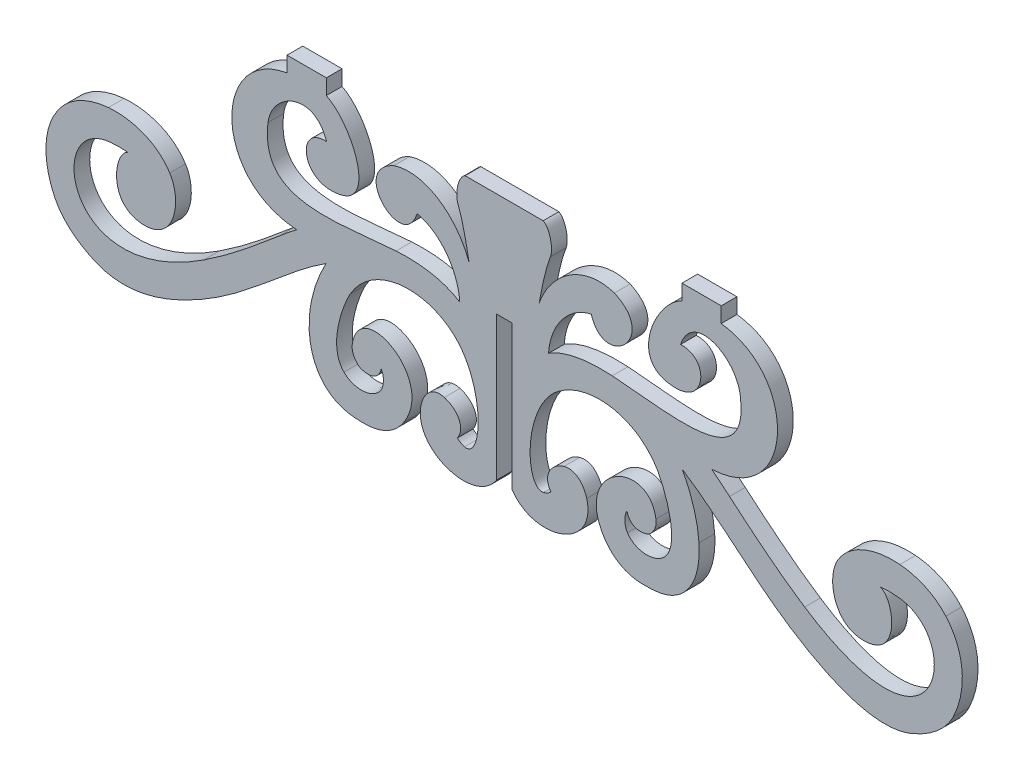
SolidWorks part; units mm, degrees
ref_plane "Plano frontal" through (0, 0, 0) normal (0, 0, 1) x (1, 0, 0)
ref_plane "Plano superior" through (0, 0, 0) normal (0, 1, 0) x (1, 0, 0)
ref_plane "Plano direito" through (0, 0, 0) normal (1, 0, 0) x (0, 0, -1)
sketch "Model" plane through (0, 0, 0) normal (0, 0, 1) x (1, 0, 0)
  line L0 (-6.7223, 87.0948) -> (1.611, 87.0948)
  line L3941 (25.0819, 87.0936) -> (25.0819, 89.0522)
  line L3942 (25.0819, 89.0522) -> (20.0819, 89.0522)
  line L3943 (20.0819, 89.0522) -> (20.0819, 87.0936)
  line L3944 (2.4147, 87.0948) -> (1.611, 87.0948)
  line L3947 (-6.7223, 87.0948) -> (-7.526, 87.0948)
  line L3948 (-25.1933, 87.0941) -> (-25.1933, 89.0522)
  line L3949 (-25.1933, 89.0522) -> (-30.1933, 89.0522)
  line L3950 (-30.1933, 89.0522) -> (-30.1933, 87.0941)
  line L3951 (-3.5557, 55.4934) -> (-3.5557, 73.8415)
  line L3952 (-3.5557, 73.8415) -> (-1.5557, 73.8415)
  line L3953 (-1.5557, 73.8415) -> (-1.5557, 55.4934)
  spline S78 degree 3 poles (-1.5557, 55.4934) (1.3324, 51.1828) (9.3145, 53.9302) (7.9628, 59.2514) knots 0 0 0 0 0.010753 0.010753 0.010753 0.010753
  spline S79 degree 3 poles (7.9628, 59.2514) (7.7655, 60.0281) (6.8767, 61.8404) (5.0534, 61.3244) knots 0.010753 0.010753 0.010753 0.010753 0.021505 0.021505 0.021505 0.021505
  spline S80 degree 3 poles (5.0534, 61.3244) (3.6461, 60.926) (2.2466, 59.35) (3.3931, 57.6868) knots 0.021505 0.021505 0.021505 0.021505 0.032258 0.032258 0.032258 0.032258
  spline S81 degree 3 poles (3.3931, 57.6868) (3.1478, 57.4328) (2.8154, 57.2407) (2.481, 57.1607) knots 0.032258 0.032258 0.032258 0.032258 0.043011 0.043011 0.043011 0.043011
  spline S82 degree 3 poles (2.481, 57.1607) (0.004, 56.5684) (-0.2039, 65.9986) (4.4458, 69.3227) knots 0.043011 0.043011 0.043011 0.043011 0.053763 0.053763 0.053763 0.053763
  spline S83 degree 3 poles (4.4458, 69.3227) (8.1489, 72.0987) (14.3081, 71.5264) (17.0509, 66.7244) knots 0.053763 0.053763 0.053763 0.053763 0.064516 0.064516 0.064516 0.064516
  spline S84 degree 3 poles (17.0509, 66.7244) (18.1854, 64.6611) (19.8274, 59.7153) (17.8402, 57.7253) knots 0.064516 0.064516 0.064516 0.064516 0.075269 0.075269 0.075269 0.075269
  spline S85 degree 3 poles (17.8402, 57.7253) (16.5822, 56.4654) (14.1497, 56.5444) (13.1448, 58.067) knots 0.075269 0.075269 0.075269 0.075269 0.086022 0.086022 0.086022 0.086022
  spline S86 degree 3 poles (13.1448, 58.067) (12.7434, 58.6752) (12.6969, 59.8398) (13.0959, 60.4397) knots 0.086022 0.086022 0.086022 0.086022 0.096774 0.096774 0.096774 0.096774
  spline S87 degree 3 poles (13.0959, 60.4397) (13.1597, 59.9829) (13.6899, 58.6489) (15.4964, 59.1291) knots 0.096774 0.096774 0.096774 0.096774 0.107527 0.107527 0.107527 0.107527
  spline S88 degree 3 poles (15.4964, 59.1291) (16.2163, 59.3056) (16.9538, 60.3437) (16.7747, 61.3853) knots 0.107527 0.107527 0.107527 0.107527 0.11828 0.11828 0.11828 0.11828
  spline S89 degree 3 poles (16.7747, 61.3853) (15.7027, 67.6161) (5.9938, 62.3947) (10.2507, 55.9445) knots 0.11828 0.11828 0.11828 0.11828 0.129032 0.129032 0.129032 0.129032
  spline S90 degree 3 poles (10.2507, 55.9445) (11.3104, 54.3388) (12.9835, 53.4391) (14.8163, 53.3639) knots 0.129032 0.129032 0.129032 0.129032 0.139785 0.139785 0.139785 0.139785
  spline S91 degree 3 poles (14.8163, 53.3639) (17.0037, 53.2741) (18.8296, 53.5898) (20.2685, 55.0308) knots 0.139785 0.139785 0.139785 0.139785 0.150538 0.150538 0.150538 0.150538
  spline S92 degree 3 poles (20.2685, 55.0308) (21.9316, 56.6963) (22.3987, 59.1658) (22.2511, 61.4956) knots 0.150538 0.150538 0.150538 0.150538 0.16129 0.16129 0.16129 0.16129
  spline S93 degree 3 poles (22.2511, 61.4956) (22.0962, 63.9402) (21.2748, 66.4447) (20.1166, 68.56) knots 0.16129 0.16129 0.16129 0.16129 0.172043 0.172043 0.172043 0.172043
  spline S94 degree 3 poles (20.1166, 68.56) (24.7894, 65.5652) (28.9378, 61.1957) (33.8482, 57.9913) knots 0.172043 0.172043 0.172043 0.172043 0.182796 0.182796 0.182796 0.182796
  spline S95 degree 3 poles (33.8482, 57.9913) (38.0156, 55.2717) (44.1924, 52.009) (49.1647, 53.947) knots 0.182796 0.182796 0.182796 0.182796 0.193548 0.193548 0.193548 0.193548
  spline S96 degree 3 poles (49.1647, 53.947) (51.3704, 54.8066) (53.5508, 56.3326) (54.6205, 58.5045) knots 0.193548 0.193548 0.193548 0.193548 0.204301 0.204301 0.204301 0.204301
  spline S97 degree 3 poles (54.6205, 58.5045) (56.2723, 61.8584) (56.3216, 66.11) (53.6788, 69.1304) knots 0.204301 0.204301 0.204301 0.204301 0.215054 0.215054 0.215054 0.215054
  spline S98 degree 3 poles (53.6788, 69.1304) (52.185, 70.8375) (49.9939, 71.7158) (47.8314, 71.902) knots 0.215054 0.215054 0.215054 0.215054 0.225806 0.225806 0.225806 0.225806
  spline S99 degree 3 poles (47.8314, 71.902) (44.993, 72.1464) (41.6526, 71.2075) (40.0071, 68.5733) knots 0.225806 0.225806 0.225806 0.225806 0.236559 0.236559 0.236559 0.236559
  spline S100 degree 3 poles (40.0071, 68.5733) (38.437, 66.1625) (39.309, 61.0858) (43.3399, 61.2103) knots 0.236559 0.236559 0.236559 0.236559 0.247312 0.247312 0.247312 0.247312
  spline S101 degree 3 poles (43.3399, 61.2103) (47.9822, 61.3536) (47.1577, 67.4304) (45.378, 68.1822) knots 0.247312 0.247312 0.247312 0.247312 0.258065 0.258065 0.258065 0.258065
  spline S102 degree 3 poles (45.378, 68.1822) (45.5771, 68.196) (46.0949, 68.3226) (47.5444, 68.1978) knots 0.258065 0.258065 0.258065 0.258065 0.268817 0.268817 0.268817 0.268817
  spline S103 degree 3 poles (47.5444, 68.1978) (56.1288, 67.4587) (53.2372, 49.7095) (35.7039, 61.1512) knots 0.268817 0.268817 0.268817 0.268817 0.27957 0.27957 0.27957 0.27957
  spline S104 degree 3 poles (35.7039, 61.1512) (32.3225, 63.358) (29.2308, 65.9343) (26.1424, 68.5597) knots 0.27957 0.27957 0.27957 0.27957 0.290323 0.290323 0.290323 0.290323
  spline S105 degree 3 poles (26.1424, 68.5597) (25.3878, 69.2011) (24.6507, 69.8283) (23.8569, 70.4159) knots 0.290323 0.290323 0.290323 0.290323 0.301075 0.301075 0.301075 0.301075
  spline S106 degree 3 poles (23.8569, 70.4159) (34.6371, 71.0038) (35.0189, 85.8605) (25.0819, 87.0936) knots 0.301075 0.301075 0.301075 0.301075 0.311828 0.311828 0.311828 0.311828
  spline S107 degree 3 poles (20.0819, 87.0936) (16.6077, 85.432) (12.9409, 77.0991) (19.324, 77.092) knots 0.344086 0.344086 0.344086 0.344086 0.354839 0.354839 0.354839 0.354839
  spline S108 degree 3 poles (19.324, 77.092) (23.2759, 77.0876) (23.5759, 82.3662) (19.9017, 82.1957) knots 0.354839 0.354839 0.354839 0.354839 0.365591 0.365591 0.365591 0.365591
  spline S109 degree 3 poles (19.9017, 82.1957) (21.4782, 86.8801) (26.9279, 84.3257) (27.5035, 80.4182) knots 0.365591 0.365591 0.365591 0.365591 0.376344 0.376344 0.376344 0.376344
  spline S110 degree 3 poles (27.5035, 80.4182) (28.8335, 71.3912) (18.3639, 73.948) (11.2069, 74.3959) knots 0.376344 0.376344 0.376344 0.376344 0.387097 0.387097 0.387097 0.387097
  spline S111 degree 3 poles (11.2069, 74.3959) (8.4975, 74.5655) (5.4129, 74.2948) (3.0953, 72.8221) knots 0.387097 0.387097 0.387097 0.387097 0.397849 0.397849 0.397849 0.397849
  spline S112 degree 3 poles (3.0953, 72.8221) (3.2894, 76.0459) (5.5232, 79.2191) (8.5335, 79.8535) knots 0.397849 0.397849 0.397849 0.397849 0.408602 0.408602 0.408602 0.408602
  spline S113 degree 3 poles (8.5335, 79.8535) (10.2661, 74.3684) (17.3019, 81.012) (11.4777, 83.6641) knots 0.408602 0.408602 0.408602 0.408602 0.419355 0.419355 0.419355 0.419355
  spline S114 degree 3 poles (11.4777, 83.6641) (7.6336, 84.9355) (3.4642, 82.1115) (1.9007, 77.7655) knots 0.419355 0.419355 0.419355 0.419355 0.430108 0.430108 0.430108 0.430108
  spline S115 degree 3 poles (1.9007, 77.7655) (2.1973, 79.4462) (2.7131, 82.0156) (3.3382, 83.5924) knots 0.430108 0.430108 0.430108 0.430108 0.44086 0.44086 0.44086 0.44086
  spline S116 degree 3 poles (3.3382, 83.5924) (3.7126, 84.5367) (3.2989, 86.6387) (2.4147, 87.0948) knots 0.44086 0.44086 0.44086 0.44086 0.451613 0.451613 0.451613 0.451613
  spline S118 degree 3 poles (-7.526, 87.0948) (-8.4102, 86.6387) (-8.8239, 84.5367) (-8.4495, 83.5924) knots 0.505376 0.505376 0.505376 0.505376 0.516129 0.516129 0.516129 0.516129
  spline S119 degree 3 poles (-8.4495, 83.5924) (-7.8244, 82.0156) (-7.3086, 79.4462) (-7.0121, 77.7655) knots 0.516129 0.516129 0.516129 0.516129 0.526882 0.526882 0.526882 0.526882
  spline S120 degree 3 poles (-7.0121, 77.7655) (-8.5755, 82.1115) (-12.7449, 84.9355) (-16.589, 83.6641) knots 0.526882 0.526882 0.526882 0.526882 0.537634 0.537634 0.537634 0.537634
  spline S121 degree 3 poles (-16.589, 83.6641) (-22.4132, 81.012) (-15.3774, 74.3684) (-13.6449, 79.8535) knots 0.537634 0.537634 0.537634 0.537634 0.548387 0.548387 0.548387 0.548387
  spline S122 degree 3 poles (-13.6449, 79.8535) (-10.6345, 79.2191) (-8.4007, 76.0459) (-8.2066, 72.8221) knots 0.548387 0.548387 0.548387 0.548387 0.55914 0.55914 0.55914 0.55914
  spline S123 degree 3 poles (-8.2066, 72.8221) (-10.5242, 74.2948) (-13.6088, 74.5655) (-16.3182, 74.3959) knots 0.55914 0.55914 0.55914 0.55914 0.569892 0.569892 0.569892 0.569892
  spline S124 degree 3 poles (-16.3182, 74.3959) (-23.4752, 73.948) (-33.7433, 71.3639) (-32.6149, 80.4182) knots 0.569892 0.569892 0.569892 0.569892 0.580645 0.580645 0.580645 0.580645
  spline S125 degree 3 poles (-32.6149, 80.4182) (-32.1511, 84.1391) (-26.7439, 86.7258) (-25.1674, 82.0414) knots 0.580645 0.580645 0.580645 0.580645 0.591398 0.591398 0.591398 0.591398
  spline S126 degree 3 poles (-25.1674, 82.0414) (-28.8415, 82.2119) (-28.5416, 76.9333) (-24.5897, 76.9377) knots 0.591398 0.591398 0.591398 0.591398 0.602151 0.602151 0.602151 0.602151
  spline S127 degree 3 poles (-24.5897, 76.9377) (-18.2058, 76.9448) (-21.7201, 85.433) (-25.1933, 87.0941) knots 0.602151 0.602151 0.602151 0.602151 0.612903 0.612903 0.612903 0.612903
  spline S128 degree 3 poles (-30.1933, 87.0941) (-39.689, 85.4201) (-39.8369, 71.1802) (-28.9683, 70.4159) knots 0.645161 0.645161 0.645161 0.645161 0.655914 0.655914 0.655914 0.655914
  spline S129 degree 3 poles (-28.9683, 70.4159) (-29.7621, 69.8283) (-30.4992, 69.2011) (-31.2537, 68.5597) knots 0.655914 0.655914 0.655914 0.655914 0.666667 0.666667 0.666667 0.666667
  spline S130 degree 3 poles (-31.2537, 68.5597) (-34.3422, 65.9343) (-37.4338, 63.358) (-40.8153, 61.1512) knots 0.666667 0.666667 0.666667 0.666667 0.677419 0.677419 0.677419 0.677419
  spline S131 degree 3 poles (-40.8153, 61.1512) (-58.3485, 49.7095) (-61.2401, 67.4587) (-52.6557, 68.1978) knots 0.677419 0.677419 0.677419 0.677419 0.688172 0.688172 0.688172 0.688172
  spline S132 degree 3 poles (-52.6557, 68.1978) (-51.2062, 68.3226) (-50.6884, 68.196) (-50.4894, 68.1822) knots 0.688172 0.688172 0.688172 0.688172 0.698925 0.698925 0.698925 0.698925
  spline S133 degree 3 poles (-50.4894, 68.1822) (-52.269, 67.4304) (-53.0935, 61.3536) (-48.4513, 61.2103) knots 0.698925 0.698925 0.698925 0.698925 0.709677 0.709677 0.709677 0.709677
  spline S134 degree 3 poles (-48.4513, 61.2103) (-44.4203, 61.0858) (-43.5483, 66.1625) (-45.1185, 68.5733) knots 0.709677 0.709677 0.709677 0.709677 0.72043 0.72043 0.72043 0.72043
  spline S135 degree 3 poles (-45.1185, 68.5733) (-46.764, 71.2075) (-50.1044, 72.1464) (-52.9427, 71.902) knots 0.72043 0.72043 0.72043 0.72043 0.731183 0.731183 0.731183 0.731183
  spline S136 degree 3 poles (-52.9427, 71.902) (-55.1052, 71.7158) (-57.2964, 70.8375) (-58.7901, 69.1304) knots 0.731183 0.731183 0.731183 0.731183 0.741935 0.741935 0.741935 0.741935
  spline S137 degree 3 poles (-58.7901, 69.1304) (-61.433, 66.11) (-61.3836, 61.8584) (-59.7318, 58.5045) knots 0.741935 0.741935 0.741935 0.741935 0.752688 0.752688 0.752688 0.752688
  spline S138 degree 3 poles (-59.7318, 58.5045) (-58.6621, 56.3326) (-56.4817, 54.8066) (-54.2761, 53.947) knots 0.752688 0.752688 0.752688 0.752688 0.763441 0.763441 0.763441 0.763441
  spline S139 degree 3 poles (-54.2761, 53.947) (-49.3037, 52.009) (-43.127, 55.2717) (-38.9596, 57.9913) knots 0.763441 0.763441 0.763441 0.763441 0.774194 0.774194 0.774194 0.774194
  spline S140 degree 3 poles (-38.9596, 57.9913) (-34.0491, 61.1957) (-29.9008, 65.5652) (-25.2279, 68.56) knots 0.774194 0.774194 0.774194 0.774194 0.784946 0.784946 0.784946 0.784946
  spline S141 degree 3 poles (-25.2279, 68.56) (-26.3861, 66.4447) (-27.2075, 63.9402) (-27.3624, 61.4956) knots 0.784946 0.784946 0.784946 0.784946 0.795699 0.795699 0.795699 0.795699
  spline S142 degree 3 poles (-27.3624, 61.4956) (-27.5101, 59.1658) (-27.0429, 56.6963) (-25.3799, 55.0308) knots 0.795699 0.795699 0.795699 0.795699 0.806452 0.806452 0.806452 0.806452
  spline S143 degree 3 poles (-25.3799, 55.0308) (-23.941, 53.5898) (-22.1151, 53.2741) (-19.9277, 53.3639) knots 0.806452 0.806452 0.806452 0.806452 0.817204 0.817204 0.817204 0.817204
  spline S144 degree 3 poles (-19.9277, 53.3639) (-18.0948, 53.4391) (-16.4217, 54.3388) (-15.362, 55.9445) knots 0.817204 0.817204 0.817204 0.817204 0.827957 0.827957 0.827957 0.827957
  spline S145 degree 3 poles (-15.362, 55.9445) (-11.1052, 62.3947) (-20.814, 67.6161) (-21.886, 61.3853) knots 0.827957 0.827957 0.827957 0.827957 0.83871 0.83871 0.83871 0.83871
  spline S146 degree 3 poles (-21.886, 61.3853) (-22.0651, 60.3437) (-21.3276, 59.3056) (-20.6077, 59.1291) knots 0.83871 0.83871 0.83871 0.83871 0.849462 0.849462 0.849462 0.849462
  spline S147 degree 3 poles (-20.6077, 59.1291) (-18.8012, 58.6489) (-18.271, 59.9829) (-18.2072, 60.4397) knots 0.849462 0.849462 0.849462 0.849462 0.860215 0.860215 0.860215 0.860215
  spline S148 degree 3 poles (-18.2072, 60.4397) (-17.8082, 59.8398) (-17.8547, 58.6752) (-18.2562, 58.067) knots 0.860215 0.860215 0.860215 0.860215 0.870968 0.870968 0.870968 0.870968
  spline S149 degree 3 poles (-18.2562, 58.067) (-19.261, 56.5444) (-21.6935, 56.4654) (-22.9516, 57.7253) knots 0.870968 0.870968 0.870968 0.870968 0.88172 0.88172 0.88172 0.88172
  spline S150 degree 3 poles (-22.9516, 57.7253) (-24.9387, 59.7153) (-23.2967, 64.6611) (-22.1622, 66.7244) knots 0.88172 0.88172 0.88172 0.88172 0.892473 0.892473 0.892473 0.892473
  spline S151 degree 3 poles (-22.1622, 66.7244) (-19.4194, 71.5264) (-13.2602, 72.0987) (-9.5572, 69.3227) knots 0.892473 0.892473 0.892473 0.892473 0.903226 0.903226 0.903226 0.903226
  spline S152 degree 3 poles (-9.5572, 69.3227) (-4.9074, 65.9986) (-5.1153, 56.5684) (-7.5923, 57.1607) knots 0.903226 0.903226 0.903226 0.903226 0.913978 0.913978 0.913978 0.913978
  spline S153 degree 3 poles (-7.5923, 57.1607) (-7.9267, 57.2407) (-8.2591, 57.4328) (-8.5045, 57.6868) knots 0.913978 0.913978 0.913978 0.913978 0.924731 0.924731 0.924731 0.924731
  spline S154 degree 3 poles (-8.5045, 57.6868) (-7.3579, 59.35) (-8.7574, 60.926) (-10.1647, 61.3244) knots 0.924731 0.924731 0.924731 0.924731 0.935484 0.935484 0.935484 0.935484
  spline S155 degree 3 poles (-10.1647, 61.3244) (-11.988, 61.8404) (-12.8768, 60.0281) (-13.0741, 59.2514) knots 0.935484 0.935484 0.935484 0.935484 0.946237 0.946237 0.946237 0.946237
  spline S156 degree 3 poles (-13.0741, 59.2514) (-14.4259, 53.9302) (-6.4437, 51.1828) (-3.5557, 55.4934) knots 0.946237 0.946237 0.946237 0.946237 0.956989 0.956989 0.956989 0.956989
extrude "Ressalto-extrusão2" add sketch "Model" along normal mid plane 2
